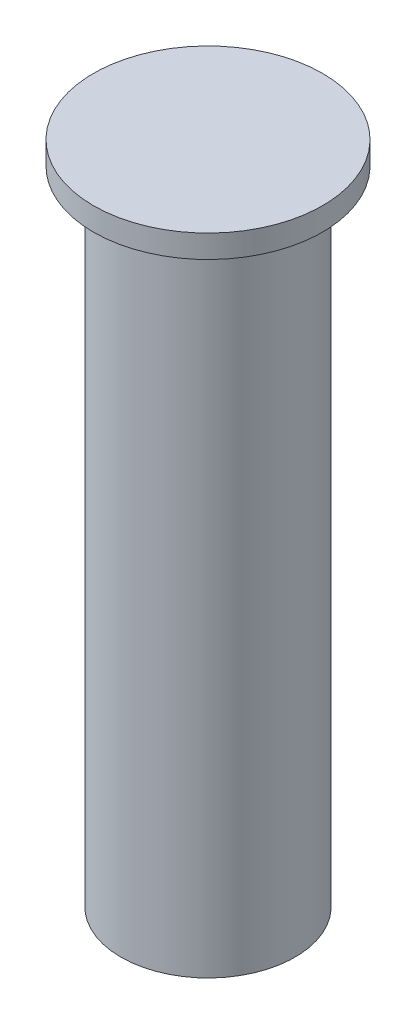
SolidWorks part; units mm, degrees
ref_plane "Front Plane" through (0, 0, 0) normal (0, 0, 1) x (1, 0, 0)
ref_plane "Top Plane" through (0, 0, 0) normal (0, 1, 0) x (1, 0, 0)
ref_plane "Right Plane" through (0, 0, 0) normal (1, 0, 0) x (0, 0, -1)
sketch "Sketch1" plane through (0, 0, 0) normal (0, 1, 0) x (1, 0, 0)
  circle A0 centre (0, 0) radius 190
  dimension "D1" = 380
extrude "Boss-Extrude1" add sketch "Sketch1" along normal blind 1400
sketch "Sketch2" plane through (0, 1400, 0) normal (0, 1, 0) x (1, 0, 0)
  circle A0 centre (0, 0) radius 250
  dimension "D1" = 500
extrude "Boss-Extrude2" add sketch "Sketch2" along normal blind 50
